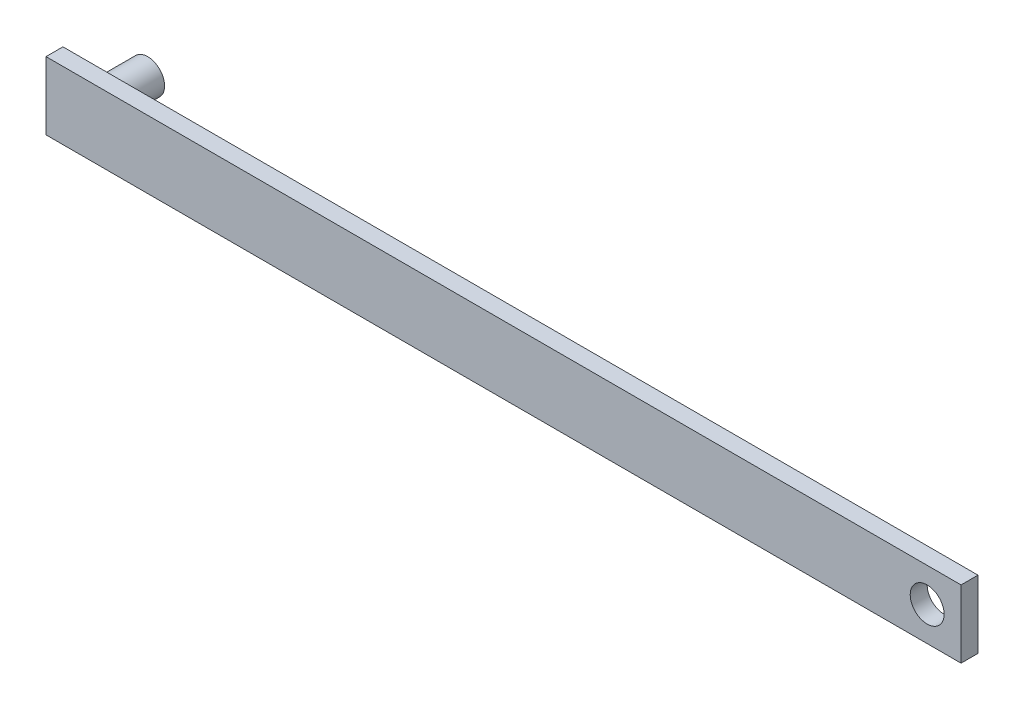
SolidWorks part; units mm, degrees
ref_plane "Front Plane" through (0, 0, 0) normal (0, 0, 1) x (1, 0, 0)
ref_plane "Top Plane" through (0, 0, 0) normal (0, 1, 0) x (1, 0, 0)
ref_plane "Right Plane" through (0, 0, 0) normal (1, 0, 0) x (0, 0, -1)
sketch "Sketch1" plane through (0, 0, 0) normal (0, 0, 1) x (1, 0, 0)
  line L0 (0, 125.8218) -> (0, -123.4972) construction
  line L1 (-208.0564, 0) -> (178.9983, 0) construction
  line L3 (-135, 10) -> (135, 10)
  line L4 (-135, 10) -> (-135, -10)
  line L5 (-135, -10) -> (135, -10)
  line L6 (135, 10) -> (135, -10)
  point P5 (0, 0)
  dimension "D1" = 270
  dimension "D2" = 135
  dimension "D3" = 20
  dimension "D4" = 10
extrude "Boss-Extrude1" add sketch "Sketch1" along normal blind 5
sketch "Sketch2" plane through (0, 0, 0) normal (0, 0, -1) x (-1, 0, 0)
  line L0 (-135, -10) -> (-135, 10) construction
  circle A0 centre (-125, 0) radius 5
  dimension "D1" = 10
extrude "Cut-Extrude1" cut sketch "Sketch2" against normal blind 5
sketch "Sketch3" plane through (0, 0, 0) normal (0, 0, -1) x (-1, 0, 0)
  line L0 (135, 10) -> (135, -10) construction
  circle A0 centre (125, 0) radius 5
  dimension "D1" = 10
extrude "Boss-Extrude2" add sketch "Sketch3" along normal blind 15
